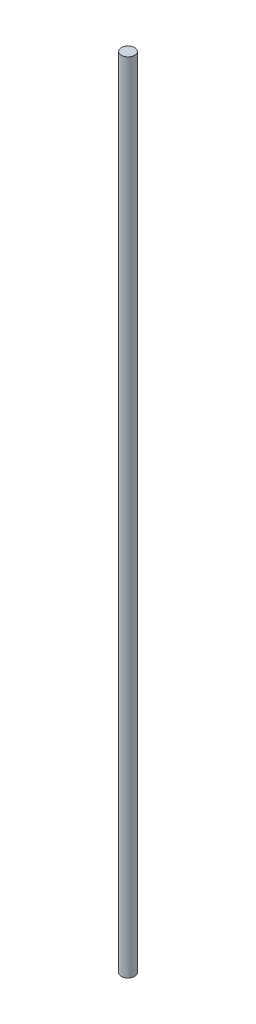
SolidWorks part; units mm, degrees
material "Alloy Steel"
ref_plane "Front Plane" through (0, 0, 0) normal (0, 0, 1) x (1, 0, 0)
ref_plane "Top Plane" through (0, 0, 0) normal (0, 1, 0) x (1, 0, 0)
ref_plane "Right Plane" through (0, 0, 0) normal (1, 0, 0) x (0, 0, -1)
sketch "Sketch1" plane through (0, 0, 0) normal (0, 1, 0) x (1, 0, 0)
  circle A0 centre (0, 0) radius 4
  dimension "D1" = 8
extrude "Boss-Extrude1" add sketch "Sketch1" along normal blind 480
cosmetic thread "Cosmetic Thread1"
